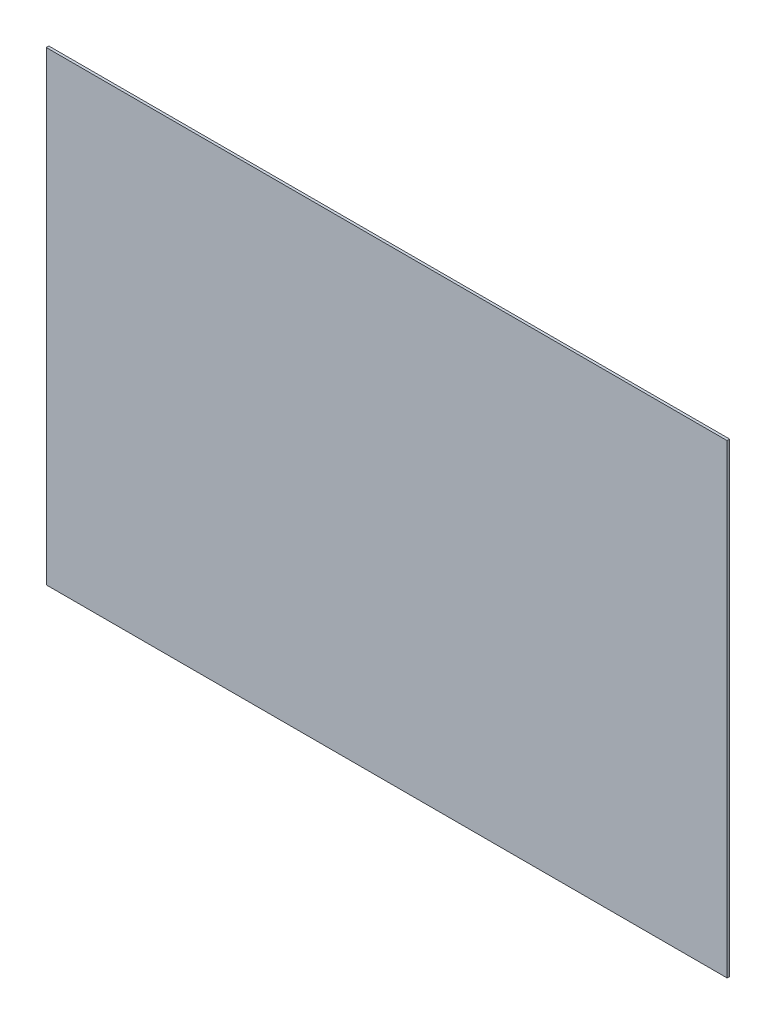
SolidWorks part; units mm, degrees
ref_plane "Front Plane" through (0, 0, 0) normal (0, 0, 1) x (1, 0, 0)
ref_plane "Top Plane" through (0, 0, 0) normal (0, 1, 0) x (1, 0, 0)
ref_plane "Right Plane" through (0, 0, 0) normal (1, 0, 0) x (0, 0, -1)
sketch "Sketch1" plane through (0, 0, 0) normal (0, 0, 1) x (1, 0, 0)
  line L1 (-395, -270) -> (395, -270)
  line L2 (-395, -270) -> (-395, 270)
  line L3 (-395, 270) -> (395, 270)
  line L4 (395, -270) -> (395, 270)
  line L5 (-395, -270) -> (395, 270) construction
  line L6 (-395, 270) -> (395, -270) construction
  point P0 (0, 0)
  dimension "D1" = 790
  dimension "D2" = 540
extrude "Boss-Extrude1" add sketch "Sketch1" along normal blind 3
